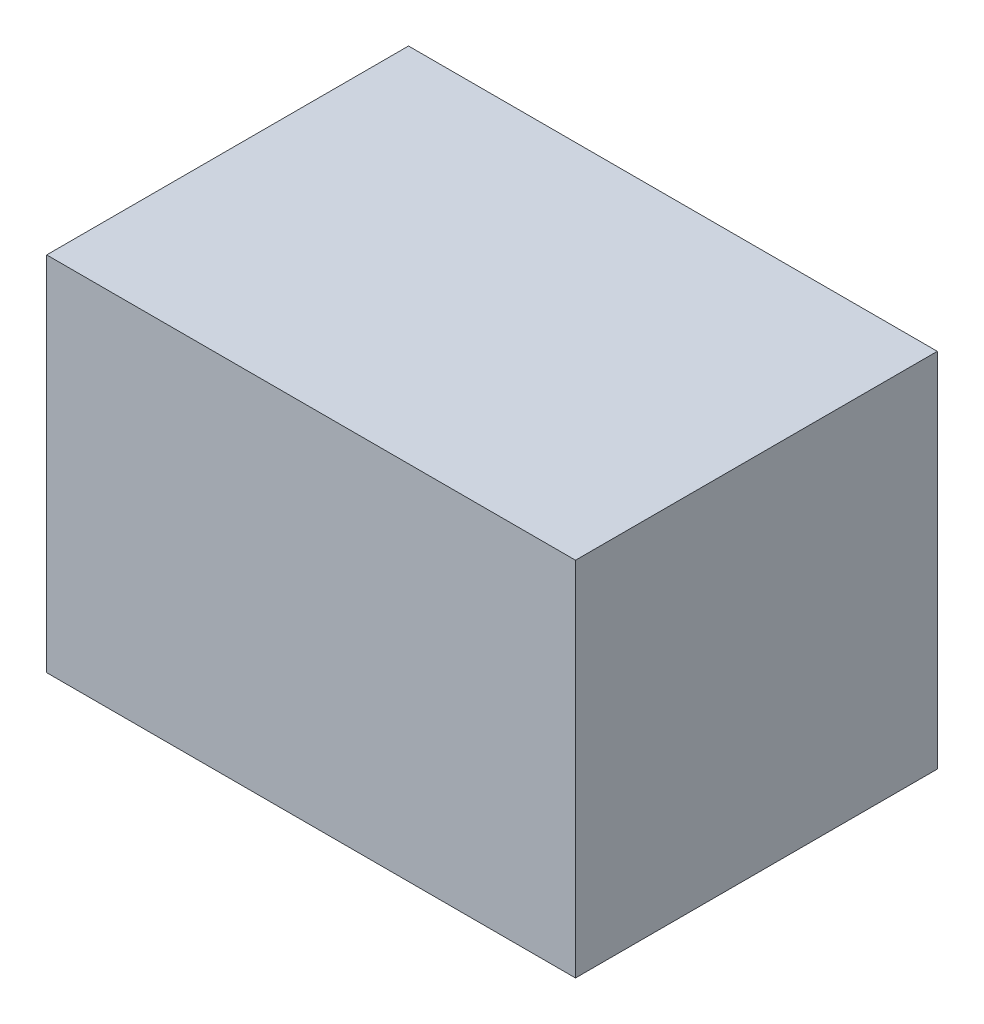
SolidWorks part; units mm, degrees
ref_plane "Ebene vorne" through (0, 0, 0) normal (0, 0, 1) x (1, 0, 0)
ref_plane "Ebene oben" through (0, 0, 0) normal (0, 1, 0) x (1, 0, 0)
ref_plane "Ebene rechts" through (0, 0, 0) normal (1, 0, 0) x (0, 0, -1)
sketch "Skizze1" plane through (0, 0, 0) normal (0, 0, 1) x (1, 0, 0)
  line L1 (-47.5, -32.5) -> (47.5, -32.5)
  line L2 (-47.5, -32.5) -> (-47.5, 32.5)
  line L3 (-47.5, 32.5) -> (47.5, 32.5)
  line L4 (47.5, -32.5) -> (47.5, 32.5)
  line L5 (-47.5, -32.5) -> (47.5, 32.5) construction
  line L6 (-47.5, 32.5) -> (47.5, -32.5) construction
  point P0 (0, 0)
  dimension "D1" = 65
  dimension "D2" = 95
extrude "Aufsatz-Linear austragen1" add sketch "Skizze1" along normal blind 65
